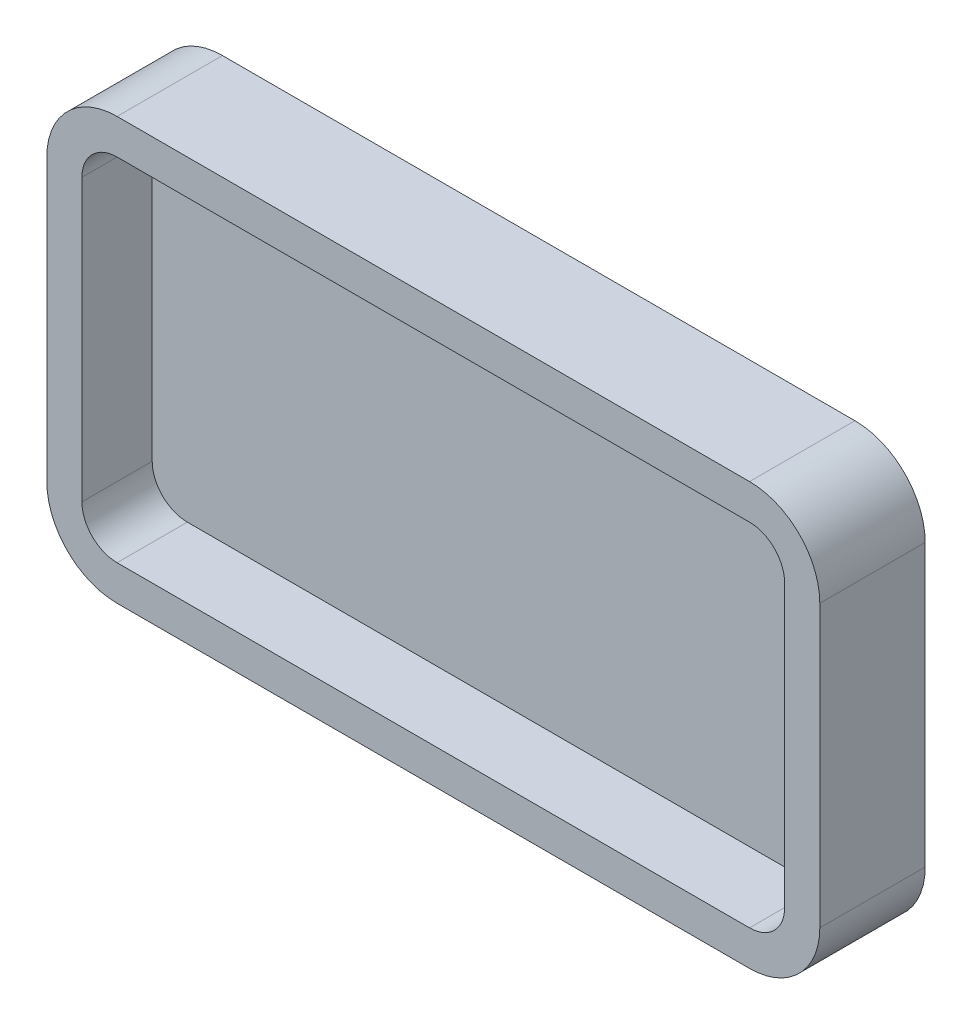
SolidWorks part; units mm, degrees
ref_plane "Plan de face" through (0, 0, 0) normal (0, 0, 1) x (1, 0, 0)
ref_plane "Plan de dessus" through (0, 0, 0) normal (0, 1, 0) x (1, 0, 0)
ref_plane "Plan de droite" through (0, 0, 0) normal (1, 0, 0) x (0, 0, -1)
sketch "Esquisse1" plane through (0, 0, 0) normal (0, 0, 1) x (1, 0, 0)
  line L1 (5, 0) -> (95, 0)
  line L2 (0, 5) -> (0, 45)
  line L3 (5, 50) -> (95, 50)
  line L4 (100, 5) -> (100, 45)
  arc A0 (95, 50) -> (100, 45) centre (95, 45) cw
  arc A1 (95, 0) -> (100, 5) centre (95, 5) ccw
  arc A2 (0, 45) -> (5, 50) centre (5, 45) cw
  arc A3 (5, 0) -> (0, 5) centre (5, 5) cw
  point P9 (100, 0)
  point P12 (0, 50)
  point P15 (0, 0)
  dimension "D3" = 5
  dimension "D1" = 100
  dimension "D2" = 50
extrude "Extru.-Mince3" add sketch "Esquisse1" along normal blind 15 thin
sketch "Esquisse2" plane through (0, 0, 0) normal (0, 0, 1) x (1, 0, 0)
  line L1 (5, 50) -> (95, 50)
  line L2 (0, 45) -> (0, 5)
  line L3 (5, 0) -> (95, 0)
  line L4 (100, 45) -> (100, 5)
  arc A0 (95, 50) -> (100, 45) centre (95, 45) cw
  arc A1 (95, 0) -> (100, 5) centre (95, 5) ccw
  arc A2 (0, 5) -> (5, 0) centre (5, 5) ccw
  arc A3 (5, 50) -> (0, 45) centre (5, 45) ccw
  point P6 (100, 50)
  point P11 (0, 0)
  point P14 (0, 50)
  dimension "D3" = 5
  dimension "D1" = 100
  dimension "D2" = 50
extrude "Boss.-Extru.2" add sketch "Esquisse2" along normal blind 5
